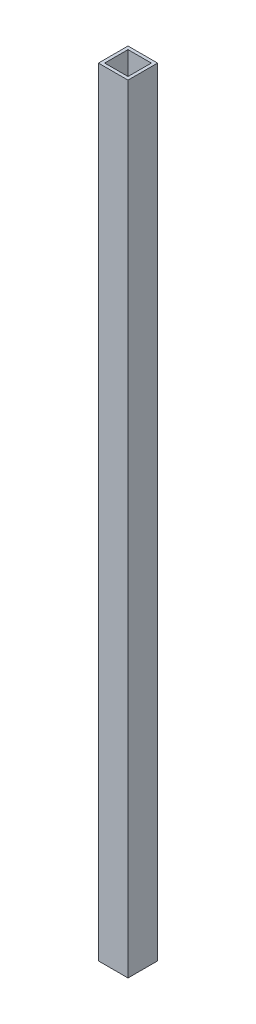
SolidWorks part; units mm, degrees
ref_plane "Front Plane" through (0, 0, 0) normal (0, 0, 1) x (1, 0, 0)
ref_plane "Top Plane" through (0, 0, 0) normal (0, 1, 0) x (1, 0, 0)
ref_plane "Right Plane" through (0, 0, 0) normal (1, 0, 0) x (0, 0, -1)
sketch "Sketch1" plane through (0, 0, 0) normal (0, 1, 0) x (1, 0, 0)
  line L1 (-9.5, -9.5) -> (9.5, -9.5)
  line L2 (-9.5, -9.5) -> (-9.5, 9.5)
  line L3 (-9.5, 9.5) -> (9.5, 9.5)
  line L4 (9.5, -9.5) -> (9.5, 9.5)
  line L5 (-9.5, -9.5) -> (9.5, 9.5) construction
  line L6 (-9.5, 9.5) -> (9.5, -9.5) construction
  point P0 (0, 0)
  dimension "D1" = 19
  dimension "D2" = 19
extrude "Extrude-Thin1" add sketch "Sketch1" along normal blind 500 thin thin type one direction reverse wall 2
